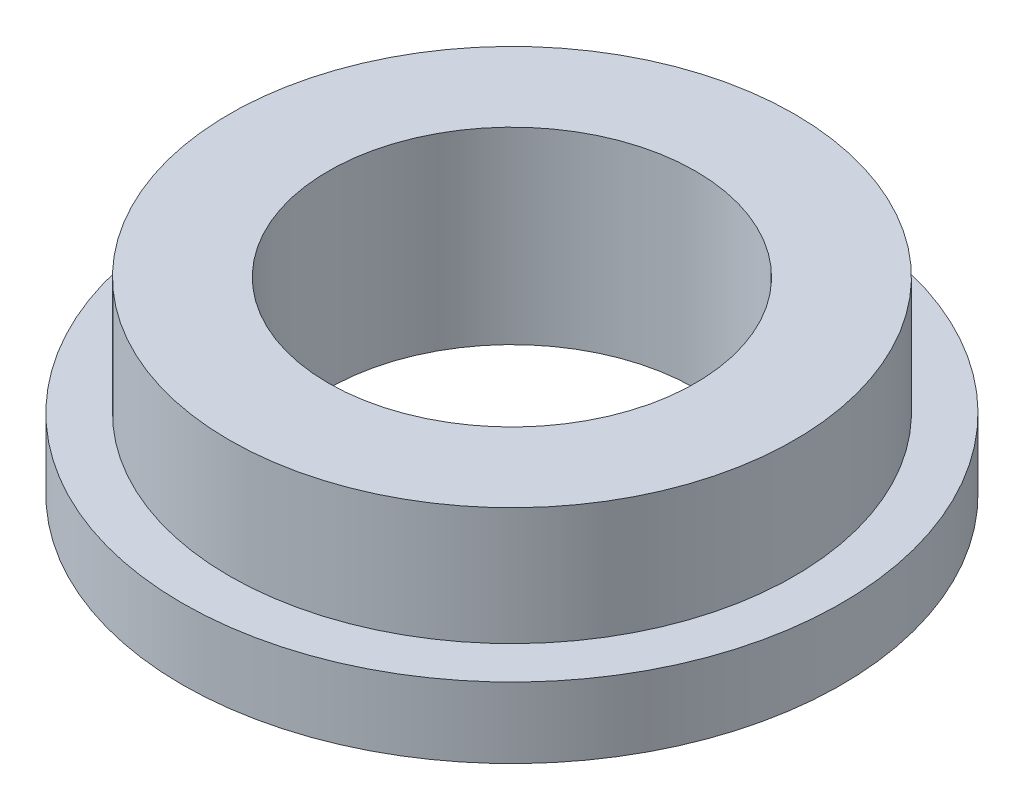
SolidWorks part; units mm, degrees
material "PTFE(普通)"
ref_plane "前视基准面" through (0, 0, 0) normal (0, 0, 1) x (1, 0, 0)
ref_plane "上视基准面" through (0, 0, 0) normal (0, 1, 0) x (1, 0, 0)
ref_plane "右视基准面" through (0, 0, 0) normal (1, 0, 0) x (0, 0, -1)
sketch "草图1" plane through (0, 0, 0) normal (0, 1, 0) x (1, 0, 0)
  circle A0 centre (0, 0) radius 7
  dimension "D1" = 14
extrude "凸台-拉伸1" add sketch "草图1" along normal blind 1.5
sketch "草图2" plane through (0, 1.5, 0) normal (0, 1, 0) x (1, 0, 0)
  circle A0 centre (0, 0) radius 6
  dimension "D1" = 12
extrude "凸台-拉伸2" add sketch "草图2" along normal blind 2.5
sketch "草图3" plane through (0, 4, 0) normal (0, 1, 0) x (1, 0, 0)
  circle A0 centre (0, 0) radius 3.9
  dimension "D1" = 7.8
extrude "切除-拉伸1" cut sketch "草图3" against normal through all
move or copy body "实体-移动/复制1" bodies to move or copy 109 copy no translate (-171.1205, -93.5732, 270.1775)
other "冻结***"
